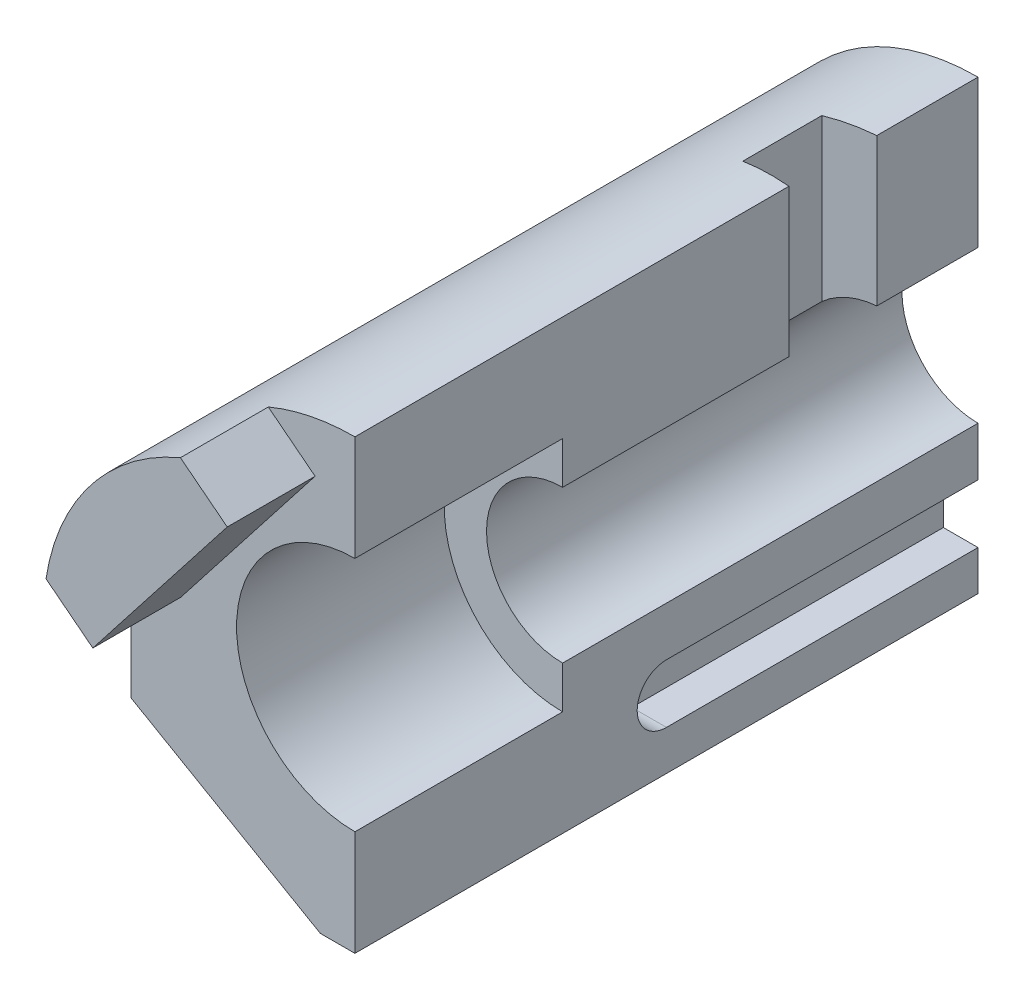
SolidWorks part; units mm, degrees
material "1060 Alloy"
ref_plane "Front Plane" through (0, 0, 0) normal (0, 0, 1) x (1, 0, 0)
ref_plane "Top Plane" through (0, 0, 0) normal (0, 1, 0) x (1, 0, 0)
ref_plane "Right Plane" through (0, 0, 0) normal (1, 0, 0) x (0, 0, -1)
sketch "Sketch1" plane through (0, 0, 0) normal (0, 0, 1) x (1, 0, 0)
  line L0 (0, 0) -> (-13, 0)
  line L1 (-13, 0) -> (-84, 40.9919)
  line L2 (-84, 40.9919) -> (-84, 84)
  line L3 (0, 168) -> (0, 0)
  arc A0 (-84, 84) -> (0, 168) centre (0, 84) cw
  dimension "D5" = 84
  dimension "D1" = 84
  dimension "D2" = 13
  dimension "D3" = 30
  dimension "D4" = 84
extrude "Boss-Extrude1" add sketch "Sketch1" against normal blind 234
sketch "Sketch2" plane through (0, 0, 0) normal (0, 0, 1) x (1, 0, 0)
  line L0 (0, 0) -> (0, 168) construction
  circle A0 centre (0, 84) radius 44.45
  dimension "D1" = 88.9
extrude "Cut-Extrude2" cut sketch "Sketch2" against normal blind 78
sketch "Sketch3" plane through (0, 0, 0) normal (0, 0, 1) x (1, 0, 0)
  line L0 (0, 128.45) -> (0, 39.55) construction
  circle A0 centre (0, 84) radius 28.575
  dimension "D1" = 57.15
extrude "Cut-Extrude3" cut sketch "Sketch3" against normal through all
sketch "Sketch5" plane through (0, 0, 0) normal (1, 0, 0) x (0, 0, -1)
  line L0 (234, 26) -> (117, 26) construction
  line L1 (234, 0) -> (234, 55.425) construction
  line L2 (234, 15) -> (117, 15)
  line L3 (234, 37) -> (117, 37)
  line L4 (234, 0) -> (0, 0) construction
  arc A0 (234, 15) -> (234, 37) centre (234, 26) ccw
  arc A1 (117, 37) -> (117, 15) centre (117, 26) ccw
  point P4 (175.5, 26)
  dimension "D2" = 11
  dimension "D1" = 117
  dimension "D3" = 26
extrude "Cut-Extrude4" cut sketch "Sketch5" against normal blind 13
sketch "Sketch6" plane through (0, 0, 0) normal (0, 0, 1) x (1, 0, 0)
  line L0 (0, 84) -> (-66.1929, 135.7156) construction
  line L1 (-40.1885, 115.3987) -> (-14.9464, 147.7072)
  line L2 (-14.9464, 147.7072) -> (-32.5304, 161.4453)
  line L3 (-40.1885, 115.3987) -> (-65.4307, 83.0903)
  line L4 (-65.4307, 83.0903) -> (-83.0146, 96.8284)
  line L5 (-13, 0) -> (0, 0) construction
  arc A0 (0, 168) -> (-84, 84) centre (0, 84) ccw construction
  arc A1 (-32.5304, 161.4453) -> (-83.0146, 96.8284) centre (0, 84) ccw
  dimension "D1" = 41
  dimension "D2" = 82
  dimension "D3" = 38
  dimension "D4" = 51
  dimension "D5" = 41
extrude "Boss-Extrude2" add sketch "Sketch6" along normal blind 33
ref_plane "Plane1" through (0, 168, 0) normal (0, 1, 0) x (1, 0, 0)
sketch "Sketch7" plane through (0, 168, 0) normal (0, 1, 0) x (1, 0, 0)
  line L6 (0, 196) -> (-19, 194.3377)
  line L7 (0, 234) -> (0, 0) construction
  line L8 (-19, 194.3377) -> (-19, 164.6623)
  line L9 (-19, 164.6623) -> (0, 163)
  line L10 (0, 234) -> (0, 0) construction
  line L11 (0, 163) -> (0, 196)
  dimension "D1" = 19
  dimension "D2" = 38
  dimension "D3" = 5
  dimension "D4" = 5
  dimension "D5" = 33
extrude "Cut-Extrude6" cut sketch "Sketch7" against normal up to surface (62.6568 mm away)
